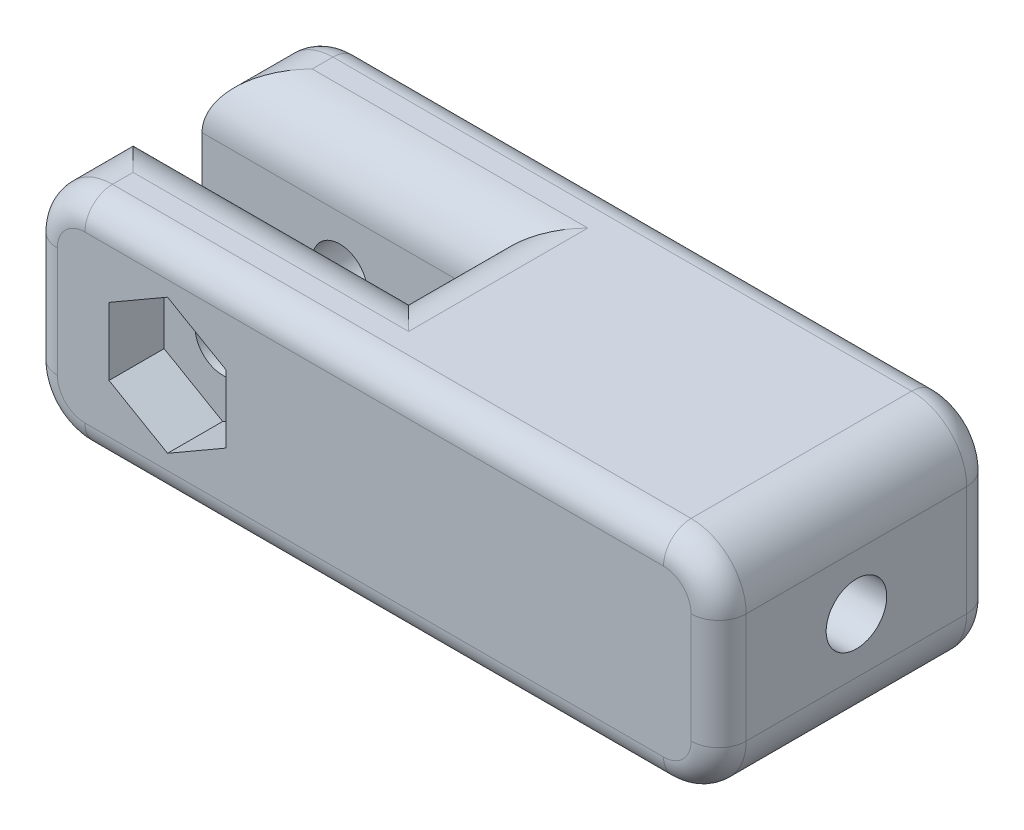
SolidWorks part; units mm, degrees
ref_plane "Front Plane" through (0, 0, 0) normal (0, 0, 1) x (1, 0, 0)
ref_plane "Top Plane" through (0, 0, 0) normal (0, 1, 0) x (1, 0, 0)
ref_plane "Right Plane" through (0, 0, 0) normal (1, 0, 0) x (0, 0, -1)
sketch "Sketch1" plane through (0, 0, 0) normal (0, 1, 0) x (1, 0, 0)
  line L0 (-25, 1.25) -> (-25, 5)
  line L1 (0, -5) -> (-25, -5)
  line L2 (0, -5) -> (0, 5)
  line L3 (0, 5) -> (-25, 5)
  line L4 (-25, -5) -> (-25, -1.25)
  line L5 (-25, 1.25) -> (-15, 1.25)
  line L7 (-25, -1.25) -> (-15, -1.25)
  line L8 (-15, 1.25) -> (-15, -1.25)
  dimension "D1" = 10
  dimension "D2" = 25
  dimension "D3" = 10
  dimension "D4" = 2.5
extrude "Boss-Extrude1" add sketch "Sketch1" along normal blind 8 contours L5 L8 L7 L4 L1 L2 L3
sketch "Sketch2" plane through (-15, 0, 0) normal (-1, 0, 0) x (0, 0, 1)
  line L2 (-1.25, 8) -> (-1.25, 0) construction
  circle A0 centre (0, 4) radius 1.1
  point P4 (-1.25, 4)
  dimension "D1" = 2.2
extrude "Cut-Extrude1" cut sketch "Sketch2" against normal through all
sketch "Sketch3" plane through (0, 0, 5) normal (0, 0, 1) x (1, 0, 0)
  line L1 (-25, 8) -> (-25, 0) construction
  circle A0 centre (-20, 4) radius 1
  point P2 (-25, 4)
  dimension "D1" = 2
  dimension "D3" = 5
extrude "Cut-Extrude2" cut sketch "Sketch3" against normal through all
sketch "Sketch4" plane through (0, 0, 5) normal (0, 0, 1) x (1, 0, 0)
  line L7 (-20, 1.5463) -> (-17.875, 2.7731)
  line L8 (-17.875, 2.7731) -> (-17.875, 5.2269)
  line L9 (-17.875, 5.2269) -> (-20, 6.4537)
  line L10 (-20, 6.4537) -> (-22.125, 5.2269)
  line L11 (-22.125, 5.2269) -> (-22.125, 2.7731)
  line L12 (-22.125, 2.7731) -> (-20, 1.5463)
  circle A0 centre (-20, 4) radius 2.125 construction
  dimension "D1" = 4.25
extrude "Cut-Extrude3" cut sketch "Sketch4" against normal blind 2
mirror "Mirror1" about plane through (0, 0, 0) normal (0, 0, 1) of "Cut-Extrude3"
fillet "Fillet1" radius 2 12 edges at (0, 8, 0) (-15, 8, 0) (-20, 8, 1.25) (-20, 8, -1.25) (0, 0, 0) (-25, 0, -3.125) (-25, 0, 3.125) (-20, 0, 1.25) (-15, 0, 0) (-20, 0, -1.25) (-25, 8, 3.125) (-25, 8, -3.125)
fillet "Fillet2" radius 1 16 edges at (-25, 4, 5) (-24.4142, 0.5858, 5) (-0.5858, 0.5858, 5) (0, 4, 5) (-0.5858, 7.4142, 5) (-25, 4, -5) (-24.4142, 0.5858, -5) (-0.5858, 0.5858, -5) (0, 4, -5) (-0.5858, 7.4142, -5) (-12.5, 0, 5) (-12.5, 0, -5) (-12.5, 8, 5) (-12.5, 8, -5) (-24.4142, 7.4142, 5) (-24.4142, 7.4142, -5)
